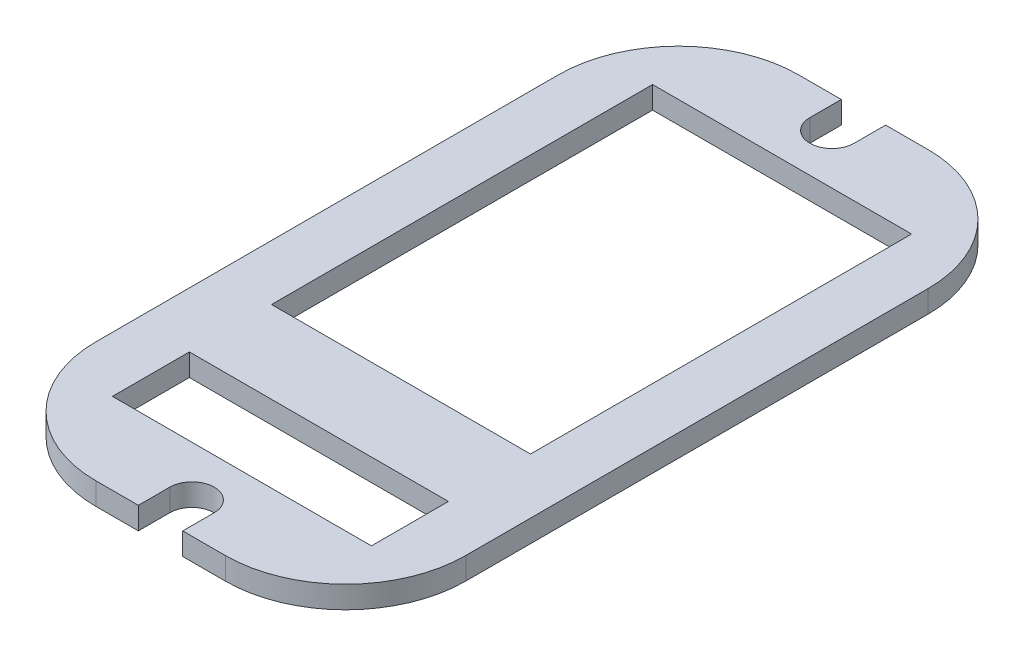
SolidWorks part; units mm, degrees
ref_plane "Front Plane" through (0, 0, 0) normal (0, 0, 1) x (1, 0, 0)
ref_plane "Top Plane" through (0, 0, 0) normal (0, 1, 0) x (1, 0, 0)
ref_plane "Right Plane" through (0, 0, 0) normal (1, 0, 0) x (0, 0, -1)
sketch "Sketch2" plane through (0, 0, 0) normal (0, 1, 0) x (1, 0, 0)
  line L0 (-0.6, 9.5) -> (-1.75, 9.5)
  line L1 (-5, 6.25) -> (-5, -6.25)
  line L2 (-1.75, -9.5) -> (-0.6, -9.5)
  line L3 (-3.5, -3) -> (3.5, -3)
  line L4 (3.5, -3) -> (3.5, 7.3)
  line L5 (3.5, 7.3) -> (-3.5, 7.3)
  line L6 (-3.5, 7.3) -> (-3.5, -3)
  line L7 (-3.5, -7.3) -> (3.5, -7.3)
  line L8 (3.5, -7.3) -> (3.5, -5.22)
  line L9 (3.5, -5.22) -> (-3.5, -5.22)
  line L10 (-3.5, -5.22) -> (-3.5, -7.3)
  line L11 (0, 8.65) -> (0, -8.65) construction
  line L12 (-0.6, -8.65) -> (-0.6, -9.5)
  line L13 (0.6, -8.65) -> (0.6, -9.5)
  line L14 (-0.6, 9.5) -> (-0.6, 8.65)
  line L15 (0.6, -9.5) -> (1.75, -9.5)
  line L16 (5, -6.25) -> (5, 6.25)
  line L17 (1.75, 9.5) -> (0.6, 9.5)
  line L18 (0, 0) -> (0, -3) construction
  line L19 (0, -3) -> (0, -5.22) construction
  line L20 (0.6, 9.5) -> (0.6, 8.65)
  arc A0 (-0.6, 8.65) -> (0.6, 8.65) centre (0, 8.65) ccw
  arc A1 (0.6, -8.65) -> (-0.6, -8.65) centre (0, -8.65) ccw
  arc A2 (-1.75, 9.5) -> (-5, 6.25) centre (-1.75, 6.25) ccw
  arc A3 (-5, -6.25) -> (-1.75, -9.5) centre (-1.75, -6.25) ccw
  arc A4 (1.75, -9.5) -> (5, -6.25) centre (1.75, -6.25) ccw
  arc A5 (5, 6.25) -> (1.75, 9.5) centre (1.75, 6.25) ccw
  point P30 (0, -5.22)
  point P31 (0, -3)
  point P38 (0, 0)
  dimension "D7" = 0.6
  dimension "D9" = 3.25
  dimension "D1" = 2.22
  dimension "D2" = 3
  dimension "D3" = 10.3
  dimension "D4" = 2.08
  dimension "D5" = 17.3
  dimension "D6" = 7
  dimension "D8" = 10
  dimension "D10" = 19
extrude "Boss-Extrude1" add sketch "Sketch2" along normal blind 0.6
